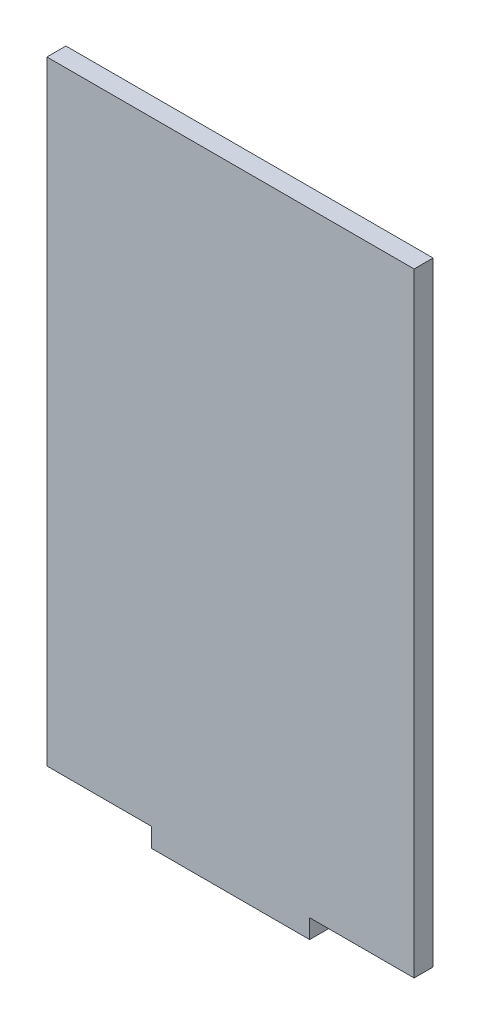
SolidWorks part; units mm, degrees
material "Maple"
ref_plane "Front Plane" through (0, 0, 0) normal (0, 0, 1) x (1, 0, 0)
ref_plane "Top Plane" through (0, 0, 0) normal (0, 1, 0) x (1, 0, 0)
ref_plane "Right Plane" through (0, 0, 0) normal (1, 0, 0) x (0, 0, -1)
sketch "Sketch1" plane through (0, 0, 0) normal (0, 0, 1) x (1, 0, 0)
  line L0 (-41, 219) -> (-41, 25)
  line L1 (-41, 219) -> (75, 219)
  line L3 (-41, 25) -> (-8, 25)
  line L5 (75, 219) -> (75, 25)
  line L6 (42, 25) -> (75, 25)
  line L17 (-8, 25) -> (-8, 19)
  line L18 (-8, 19) -> (42, 19)
  line L19 (42, 25) -> (42, 19)
  point P0 (0, 0)
  point P6 (0, -125)
  dimension "D1" = 116
  dimension "D2" = 194
  dimension "D3" = 50
  dimension "D4" = 33
  dimension "D5" = 33
  dimension "D6" = 6
extrude "Boss-Extrude1" add sketch "Sketch1" along normal blind 6
